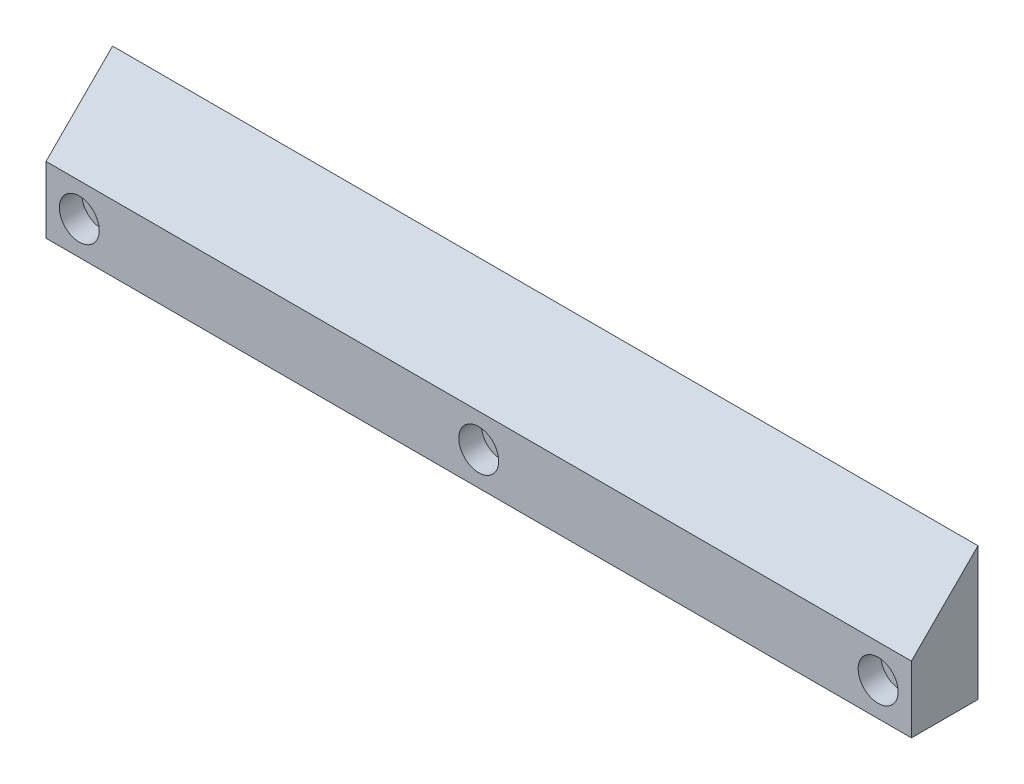
SolidWorks part; units mm, degrees
material "AISI Type 316L stainless steel"
ref_plane "Front Plane" through (0, 0, 0) normal (0, 0, 1) x (1, 0, 0)
ref_plane "Top Plane" through (0, 0, 0) normal (0, 1, 0) x (1, 0, 0)
ref_plane "Right Plane" through (0, 0, 0) normal (1, 0, 0) x (0, 0, -1)
sketch "Sketch1" plane through (0, 0, 0) normal (0, 0, 1) x (1, 0, 0)
  line L1 (-65, 0) -> (65, 0)
  line L2 (-65, 0) -> (-65, 10)
  line L3 (-65, 10) -> (65, 10)
  line L4 (65, 0) -> (65, 10)
  line L5 (-65, 0) -> (65, 10) construction
  line L6 (-65, 10) -> (65, 0) construction
  point P0 (0, 5)
  dimension "D1" = 10
  dimension "D2" = 130
extrude "Boss-Extrude1" add sketch "Sketch1" along normal blind 10
hole_wizard "CBORE for M3 Hexagon socket head cap screws1" positions "Sketch2" profile "Sketch3" counterbore size "M3" standard "GB" end condition through all
sketch "Sketch2" plane through (0, 0, 10) normal (0, 0, 1) x (1, 0, 0)
  line L0 (0, -55) -> (0, 55) construction
  line L1 (-65, 0) -> (65, 0) construction
  line L2 (-65, 10) -> (-65, 0) construction
  point P0 (-60, 5)
  point P2 (0, 5)
  point P7 (60, 5)
  dimension "D1" = 5
  dimension "D2" = 5
sketch "Sketch3" plane through (-60, 5, 10) normal (1, 0, 0) x (0, -1, 0)
  line L0 (0, 0) -> (0, 10)
  line L1 (0, 10) -> (1.6, 10)
  line L3 (1.6, 10) -> (1.6, 3.4)
  line L4 (1.6, 3.4) -> (3, 3.4)
  line L5 (3, 3.4) -> (3, 0)
  line L7 (3, 0) -> (0, 0)
  line L11 (0, -6.35) -> (0, 107.95) construction
  dimension "Thru Hole Dia." = 3.2
  dimension "Thru Hole Depth" = 10
  dimension "C'Bore Dia." = 6
  dimension "C'Bore Depth" = 3.4
sketch "Sketch4" plane through (-65, 0, 0) normal (-1, 0, 0) x (0, 0, 1)
  line L0 (10, 10) -> (0, 10)
  line L1 (0, 10) -> (0, 20)
  line L2 (0, 20) -> (10, 10)
  line L3 (0, 10) -> (0, 0) construction
  dimension "D1" = 45
extrude "Boss-Extrude2" add sketch "Sketch4" against normal up to surface (130 mm away) up to face at (65, 5, 5)
